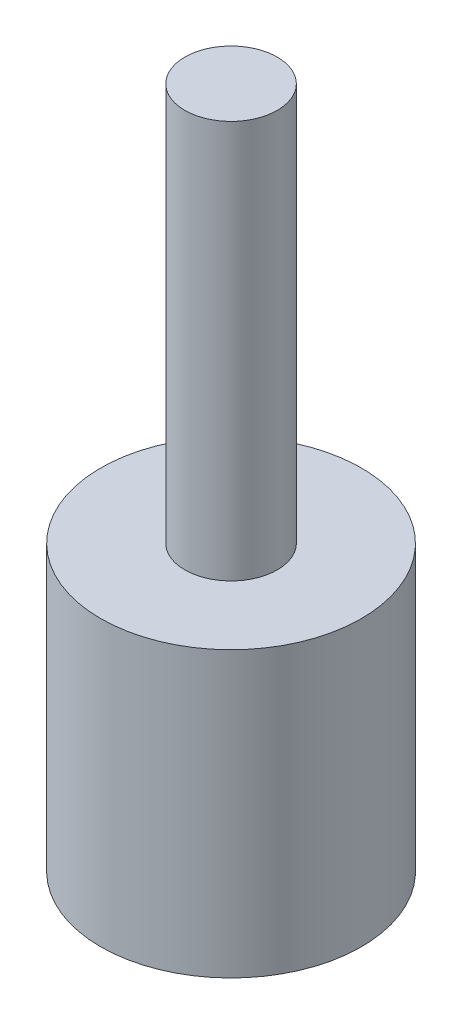
SolidWorks part; units mm, degrees
ref_plane "Front Plane" through (0, 0, 0) normal (0, 0, 1) x (1, 0, 0)
ref_plane "Top Plane" through (0, 0, 0) normal (0, 1, 0) x (1, 0, 0)
ref_plane "Right Plane" through (0, 0, 0) normal (1, 0, 0) x (0, 0, -1)
ref_plane "Plane1" through (0, 20, 0) normal (0, 1, 0) x (1, 0, 0)
sketch "AxisofRevolution" plane through (0, 0, 0) normal (0, 0, 1) x (1, 0, 0)
  line L0 (0, -1.3736) -> (0, 46.3376) construction
sketch "Sketch2" plane through (0, 0, 0) normal (0, 1, 0) x (1, 0, 0)
  circle A0 centre (0, 0) radius 9.175
  dimension "D1" = 18.35
extrude "Boss-Extrude2" add sketch "Sketch2" along direction (0, 1, 0) on the side of the normal up to surface (20 mm away) up to plane "Plane1"
sketch "Sketch3" plane through (0, 20, 0) normal (0, 1, 0) x (1, 0, 0)
  circle A0 centre (0, 0) radius 3.25
  dimension "D1" = 6.5
extrude "Boss-Extrude3" add sketch "Sketch3" along normal blind 28
sketch "Sketch4" plane through (0, 0, 0) normal (0, -1, 0) x (1, 0, 0)
  circle A0 centre (0, 0) radius 3.175
  dimension "D1" = 6.35
extrude "Cut-Extrude1" cut sketch "Sketch4" along direction (0, 1, 0) on the side against the normal blind 15 contours A0
equation "\"D1\"= 26 + 10"
equation "\"D1@Sketch2\"=6.35+12"
equation "\"D1@Sketch7\"=4"
equation "\"D1@Sketch9\"=20.5+(26-20.5)/2"
